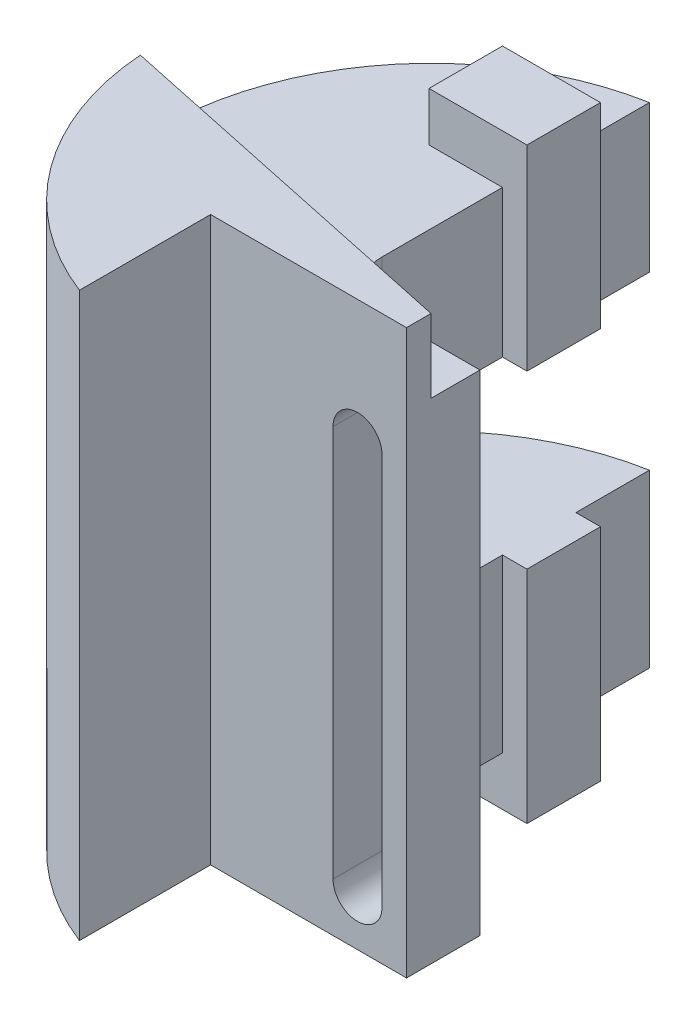
SolidWorks part; units mm, degrees
material "1060 Alloy"
ref_plane "Front Plane" through (0, 0, 0) normal (0, 0, 1) x (1, 0, 0)
ref_plane "Top Plane" through (0, 0, 0) normal (0, 1, 0) x (1, 0, 0)
ref_plane "Right Plane" through (0, 0, 0) normal (1, 0, 0) x (0, 0, -1)
sketch "Sketch1" plane through (0, 0, 0) normal (0, 1, 0) x (1, 0, 0)
  line L0 (-10, 54.5917) -> (-10, 39.5917)
  line L1 (0, -10) -> (20, -10)
  line L2 (20, -10) -> (20, -25)
  line L3 (20, -25) -> (-20, -25)
  line L4 (-20, -25) -> (-20, -51.7711)
  line L5 (-10, 39.5917) -> (-5, 39.5917)
  line L6 (-5, 39.5917) -> (-5, 24.5917)
  line L7 (-5, 24.5917) -> (-10, 24.5917)
  line L8 (-10, 24.5917) -> (-10, 0)
  arc A0 (-10, 54.5917) -> (-20, -51.7711) centre (0, 0) ccw
  arc A1 (-10, 0) -> (0, -10) centre (0, 0) ccw
  dimension "D1" = 111
  dimension "D2" = 10
  dimension "D3" = 15
  dimension "D4" = 40
  dimension "D5" = 20
  dimension "D6" = 15
  dimension "D7" = 5
  dimension "D8" = 15
extrude "Boss-Extrude1" add sketch "Sketch1" along normal blind 100
sketch "Sketch2" plane through (0, 0, 10) normal (0, 0, -1) x (-1, 0, 0)
  line L0 (-10, 90.0036) -> (-10, 10.0036) construction
  line L1 (-5, 90.0036) -> (-5, 10.0036)
  line L2 (-15, 90.0036) -> (-15, 10.0036)
  line L3 (-20, 100) -> (0, 100) construction
  line L4 (-20, 100) -> (-20, 0) construction
  arc A0 (-5, 90.0036) -> (-15, 90.0036) centre (-10, 90.0036) ccw
  arc A1 (-15, 10.0036) -> (-5, 10.0036) centre (-10, 10.0036) ccw
  point P2 (-10, 50.0036)
  dimension "D4" = 5
  dimension "D1" = 80
  dimension "D2" = 9.9964
  dimension "D3" = 10
extrude "Cut-Extrude1" cut sketch "Sketch2" against normal blind 100
sketch "Sketch3" plane through (0, 100, 0) normal (0, 1, 0) x (1, 0, 0)
  line L0 (20, -25) -> (20, -10) construction
  line L1 (-20, -51.7711) -> (-20, -25) construction
  line L2 (-20, -25) -> (20, -25) construction
  line L3 (20, -25) -> (20, -20)
  line L4 (-20, -51.7711) -> (-20, -25)
  line L5 (-20, -25) -> (20, -25)
  line L6 (20, -20) -> (-55.3569, -3.9824)
  arc A0 (-10, 54.5917) -> (-20, -51.7711) centre (0, 0) ccw construction
  arc A1 (-55.3569, -3.9824) -> (-20, -51.7711) centre (0, 0) ccw
  dimension "D1" = 5
  dimension "D2" = 78
extrude "Boss-Extrude2" add sketch "Sketch3" along normal blind 15
sketch "Sketch4" plane through (-5, 0, 0) normal (1, 0, 0) x (0, 0, -1)
  line L0 (54.5917, 100) -> (54.5917, 0) construction
  line L1 (54.5917, 70) -> (14.5917, 70)
  line L2 (54.5917, 70) -> (54.5917, 35)
  line L3 (54.5917, 35) -> (14.5917, 35)
  line L4 (14.5917, 70) -> (14.5917, 35)
  dimension "D1" = 40
  dimension "D2" = 35
  dimension "D3" = 30
extrude "Cut-Extrude2" cut sketch "Sketch4" against normal through all
sketch "Sketch5" plane through (0, 100, 0) normal (0, 1, 0) x (1, 0, 0)
  line L1 (-5, 39.5917) -> (-25, 39.5917)
  line L2 (-5, 39.5917) -> (-5, 24.5917)
  line L3 (-5, 24.5917) -> (-25, 24.5917)
  line L4 (-25, 39.5917) -> (-25, 24.5917)
  dimension "D1" = 15
  dimension "D2" = 20
extrude "Boss-Extrude3" add sketch "Sketch5" along normal blind 10
sketch "Sketch6" plane through (0, 0, 0) normal (0, -1, 0) x (1, 0, 0)
  line L1 (-5, -24.5917) -> (-25, -24.5917)
  line L2 (-5, -24.5917) -> (-5, -39.5917)
  line L3 (-5, -39.5917) -> (-25, -39.5917)
  line L4 (-25, -24.5917) -> (-25, -39.5917)
  dimension "D1" = 15
  dimension "D2" = 20
extrude "Boss-Extrude4" add sketch "Sketch6" along normal blind 10
equation "\"A\"= 50mm"
equation "\"B\"= 55mm"
equation "\"C\"= 35mm"
